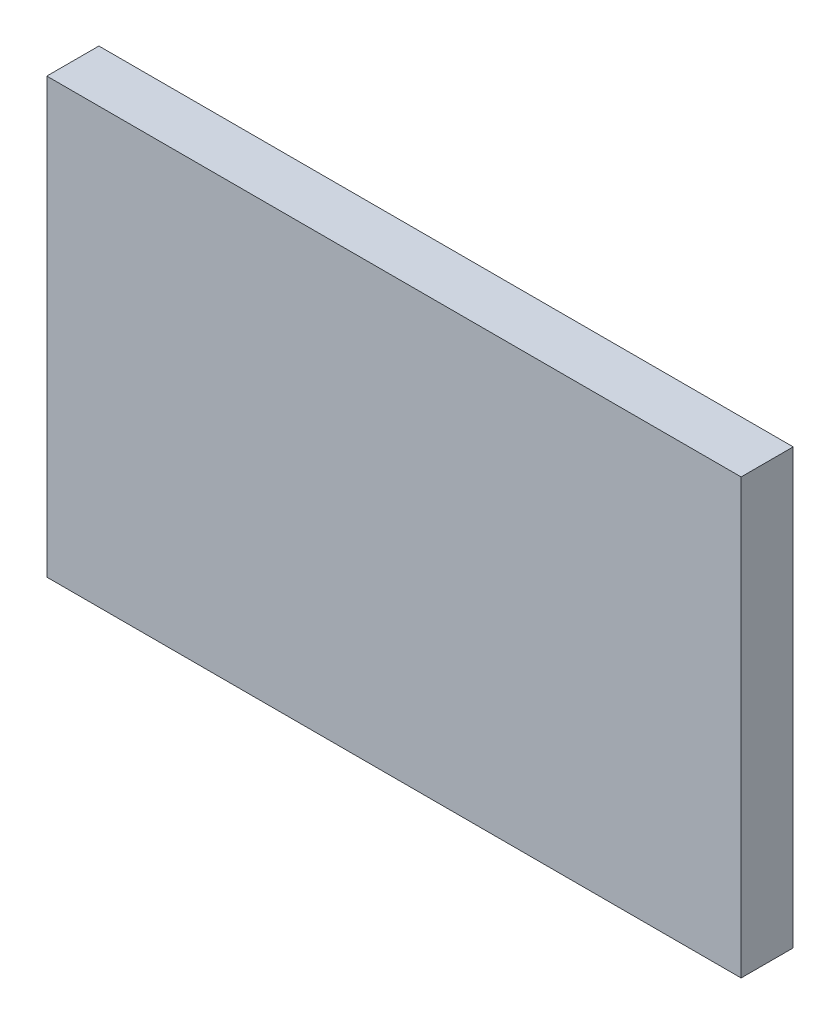
SolidWorks part; units mm, degrees
material "Acrylic (Medium-high impact)"
ref_plane "Front Plane" through (0, 0, 0) normal (0, 0, 1) x (1, 0, 0)
ref_plane "Top Plane" through (0, 0, 0) normal (0, 1, 0) x (1, 0, 0)
ref_plane "Right Plane" through (0, 0, 0) normal (1, 0, 0) x (0, 0, -1)
sketch "Sketch1" plane through (0, 0, 0) normal (0, 0, 1) x (1, 0, 0)
  line L1 (-40, 25) -> (40, 25)
  line L2 (-40, 25) -> (-40, -25)
  line L3 (-40, -25) -> (40, -25)
  line L4 (40, 25) -> (40, -25)
  line L5 (-40, 25) -> (40, -25) construction
  line L6 (-40, -25) -> (40, 25) construction
  point P0 (0, 0)
  dimension "D1" = 80
  dimension "D2" = 50
extrude "Boss-Extrude1" add sketch "Sketch1" along normal blind 6
